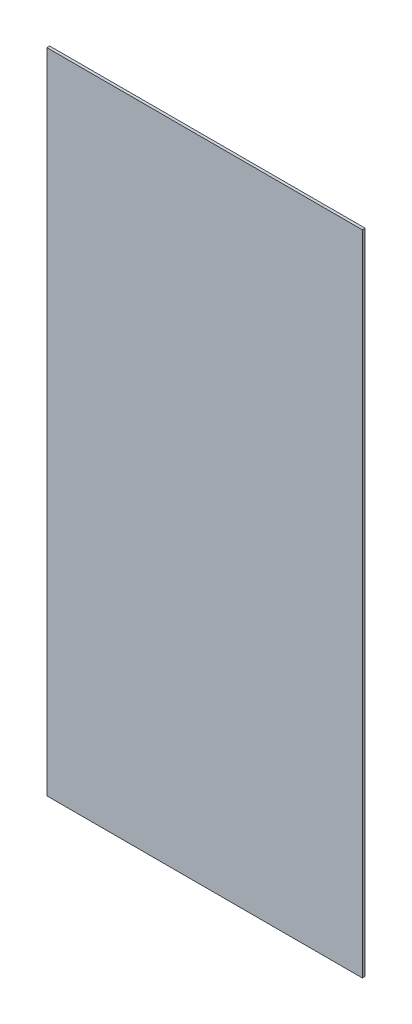
SolidWorks part; units mm, degrees
ref_plane "Front" through (0, 0, 0) normal (0, 0, 1) x (1, 0, 0)
ref_plane "Top" through (0, 0, 0) normal (0, 1, 0) x (1, 0, 0)
ref_plane "Right" through (0, 0, 0) normal (1, 0, 0) x (0, 0, -1)
sketch "Sketch1" plane through (0, 0, 0) normal (0, 0, 1) x (1, 0, 0)
  line L1 (0, 0) -> (533.4, 0)
  line L2 (0, 0) -> (0, 1095.375)
  line L3 (0, 1095.375) -> (533.4, 1095.375)
  line L4 (533.4, 0) -> (533.4, 1095.375)
extrude "Extrude1" add sketch "Sketch1" along normal blind 4.7625
